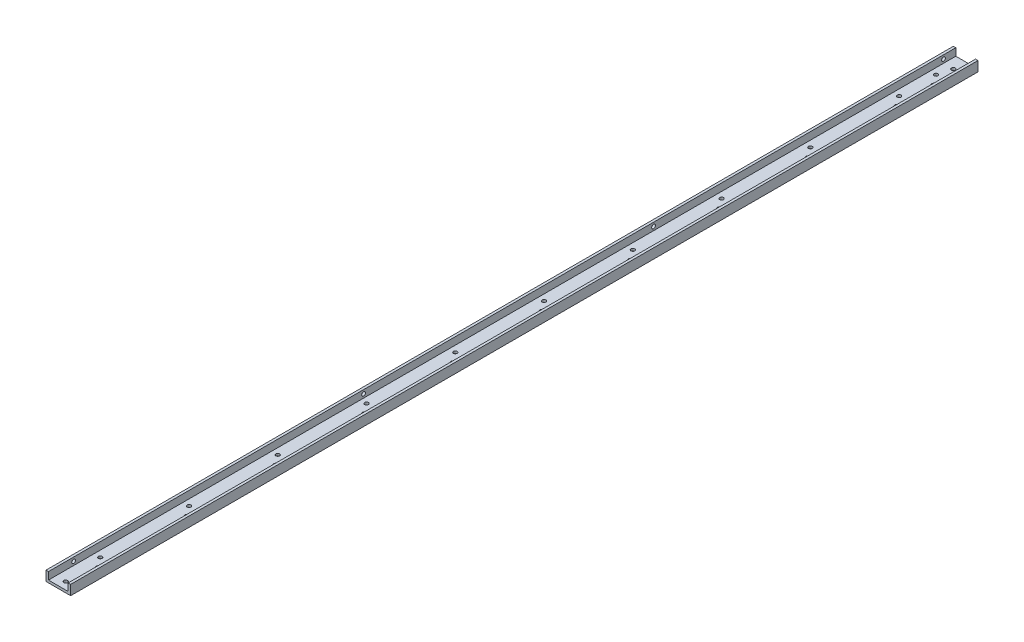
SolidWorks part; units mm, degrees
ref_plane "Front Plane" through (0, 0, 0) normal (0, 0, 1) x (1, 0, 0)
ref_plane "Top Plane" through (0, 0, 0) normal (0, 1, 0) x (1, 0, 0)
ref_plane "Right Plane" through (0, 0, 0) normal (1, 0, 0) x (0, 0, -1)
sketch "Sketch1" plane through (0, 0, 0) normal (0, 0, 1) x (1, 0, 0)
  line L0 (3.175, 3.175) -> (3.175, 12.7)
  line L1 (0, 0) -> (31.75, 0)
  line L2 (0, 0) -> (0, 12.7)
  line L4 (31.75, 0) -> (31.75, 12.7)
  line L5 (3.175, 3.175) -> (28.575, 3.175)
  line L6 (28.575, 3.175) -> (28.575, 12.7)
  line L7 (0, 12.7) -> (3.175, 12.7)
  line L8 (31.75, 12.7) -> (28.575, 12.7)
  dimension "D1" = 31.75
  dimension "D2" = 12.7
  dimension "D3" = 3.175
extrude "Boss-Extrude1" add sketch "Sketch1" along normal blind 1168.4
sketch "Sketch3" plane through (0, 3.175, 0) normal (0, 1, 0) x (1, 0, 0)
  line L0 (11.1125, -1109.6625) -> (11.1125, -1122.3625) construction
  line L1 (11.1125, -1122.3625) -> (20.6375, -1122.3625) construction
  line L2 (20.6375, -1122.3625) -> (11.1125, -1109.6625) construction
  line L3 (20.6375, -1122.3625) -> (20.6375, -1168.4) construction
  line L4 (28.575, -1168.4) -> (3.175, -1168.4) construction
  circle A1 centre (11.1125, -1109.6625) radius 2.413
  circle A3 centre (20.6375, -1122.3625) radius 2.413
  dimension "D1" = 9.525
  dimension "D2" = 12.7
  dimension "D3" = 46.0375
extrude "Cut-Extrude1" cut sketch "Sketch3" against normal up to next
sketch "Sketch4" plane through (0, 3.175, 0) normal (0, 1, 0) x (1, 0, 0)
  line L0 (15.875, -1168.4) -> (15.875, -1158.875) construction
  line L1 (28.575, -1168.4) -> (3.175, -1168.4) construction
  circle A0 centre (15.875, -1158.875) radius 2.413
  dimension "D2" = 4.826
  dimension "D1" = 9.525
extrude "Cut-Extrude2" cut sketch "Sketch4" against normal up to next
pattern_linear "LPattern1" count 10 spacing 114.3 along (0, 0, -1) of "Cut-Extrude1"
sketch "Sketch5" plane through (0, 0, 0) normal (-1, 0, 0) x (0, 0, 1)
  circle A0 centre (15.875, 7.9375) radius 2.413 construction
  circle A1 centre (15.875, 7.9375) radius 2.413
  circle A2 centre (389.255, 7.9375) radius 2.413 construction
  circle A3 centre (389.255, 7.9375) radius 2.413
  circle A4 centre (762.635, 7.9375) radius 2.413 construction
  circle A5 centre (762.635, 7.9375) radius 2.413
  circle A6 centre (1136.015, 7.9375) radius 2.413 construction
  circle A7 centre (1136.015, 7.9375) radius 2.413
extrude "Cut-Extrude3" cut sketch "Sketch5" against normal up to next
sketch "Sketch6" plane through (0, 0, 0) normal (0, -1, 0) x (1, 0, 0)
  circle A0 centre (11.1125, 33.3375) radius 2.413 construction
  circle A1 centre (11.1125, 33.3375) radius 2.413
  circle A2 centre (20.6375, 46.0375) radius 2.413 construction
  circle A3 centre (20.6375, 46.0375) radius 2.413
extrude "Cut-Extrude4" cut sketch "Sketch6" against normal up to next
sketch "Sketch7" plane through (0, 3.175, 0) normal (0, 1, 0) x (1, 0, 0)
  line L0 (15.875, 0) -> (15.875, -15.875) construction
  line L1 (28.575, 0) -> (3.175, 0) construction
  circle A0 centre (15.875, -15.875) radius 2.413
  dimension "D2" = 4.826
  dimension "D1" = 15.875
extrude "Cut-Extrude5" cut sketch "Sketch7" against normal up to next
